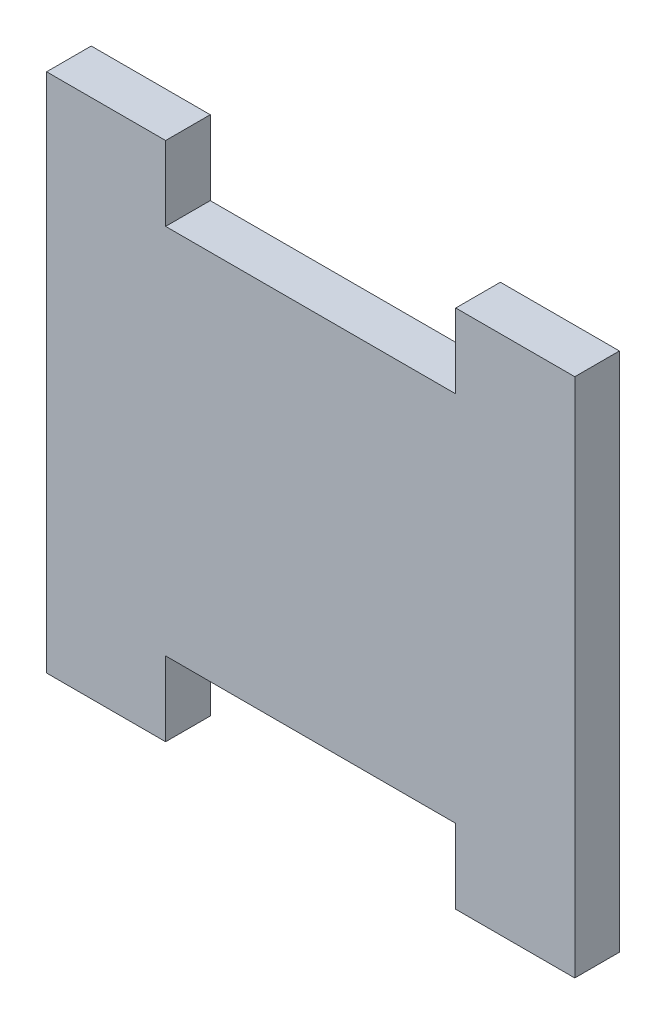
SolidWorks part; units mm, degrees
ref_plane "Plano frontal" through (0, 0, 0) normal (0, 0, 1) x (1, 0, 0)
ref_plane "Plano superior" through (0, 0, 0) normal (0, 1, 0) x (1, 0, 0)
ref_plane "Plano direito" through (0, 0, 0) normal (1, 0, 0) x (0, 0, -1)
sketch "Esboço1" plane through (0, 0, 0) normal (0, 0, 1) x (1, 0, 0)
  line L0 (-9.75, 13.0042) -> (9.75, 13.0042)
  line L1 (9.75, 13.0042) -> (9.75, 18.0042)
  line L3 (9.75, 18.0042) -> (17.75, 18.0042)
  line L7 (17.75, 18.0042) -> (17.75, 13.0042)
  line L9 (-9.75, 13.0042) -> (-9.75, 18.0042)
  line L10 (-9.75, 18.0042) -> (-17.75, 18.0042)
  line L11 (-17.75, 18.0042) -> (-17.75, 13.0042)
  line L16 (0, -11.9958) -> (-9.75, -11.9958)
  line L17 (-9.75, -11.9958) -> (-9.75, -16.9958)
  line L18 (-9.75, -16.9958) -> (-17.75, -16.9958)
  line L19 (-17.75, -16.9958) -> (-17.75, 13.0042)
  line L20 (17.75, 13.0042) -> (17.75, -16.9958)
  line L21 (17.75, -16.9958) -> (9.75, -16.9958)
  line L22 (9.75, -16.9958) -> (9.75, -11.9958)
  line L23 (9.75, -11.9958) -> (0, -11.9958)
extrude "Ressalto-extrusão1" add sketch "Esboço1" along normal blind 3
